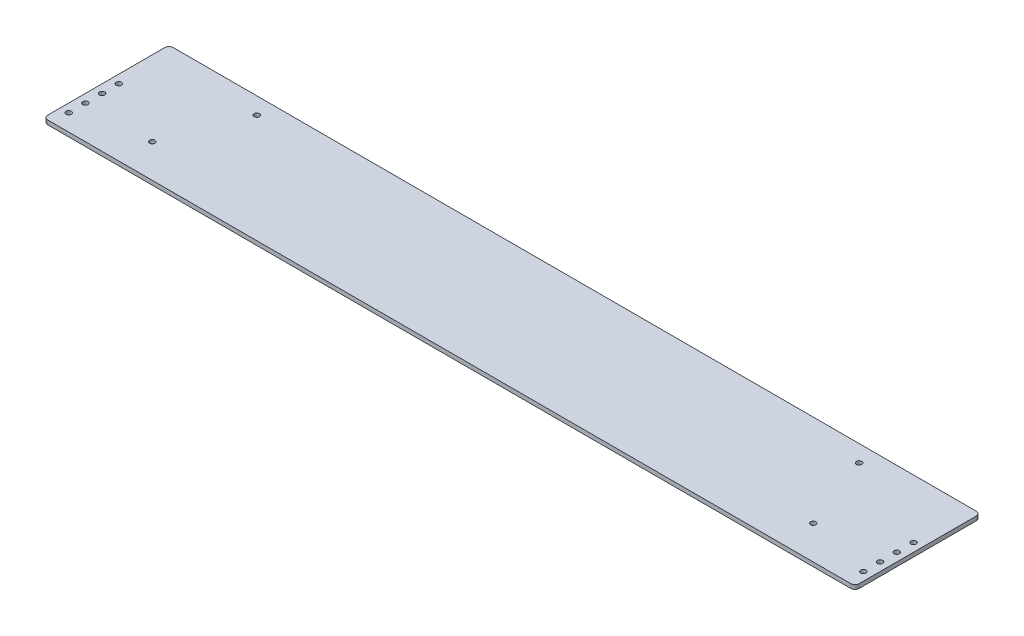
SolidWorks part; units mm, degrees
material "PC High Viscosity"
ref_plane "Front Plane" through (0, 0, 0) normal (0, 0, 1) x (1, 0, 0)
ref_plane "Top Plane" through (0, 0, 0) normal (0, 1, 0) x (1, 0, 0)
ref_plane "Right Plane" through (0, 0, 0) normal (1, 0, 0) x (0, 0, -1)
sketch "Sketch1" plane through (0, 0, 0) normal (0, 1, 0) x (1, 0, 0)
  line L0 (-301.625, 3.175) -> (-301.625, -34.925) construction
  line L1 (-307.975, -47.625) -> (307.975, -47.625)
  line L2 (-307.975, -47.625) -> (-307.975, 47.625)
  line L3 (-307.975, 47.625) -> (307.975, 47.625)
  line L4 (307.975, -47.625) -> (307.975, 47.625)
  line L5 (-307.975, -47.625) -> (307.975, 47.625) construction
  line L6 (-307.975, 47.625) -> (307.975, -47.625) construction
  line L7 (0, 47.625) -> (0, -47.625) construction
  circle A2 centre (-301.625, 3.175) radius 2.0193
  circle A3 centre (-301.625, -9.525) radius 2.0193
  circle A4 centre (-301.625, -22.225) radius 2.0193
  circle A5 centre (-301.625, -34.925) radius 2.0193
  circle A6 centre (301.625, -34.925) radius 2.0193
  circle A7 centre (301.625, -22.225) radius 2.0193
  circle A8 centre (301.625, -9.525) radius 2.0193
  circle A9 centre (301.625, 3.175) radius 2.0193
  point P0 (0, 0)
  dimension "D3" = 6.35
  dimension "D4" = 4.0386
  dimension "D5" = 4
  dimension "D6" = 44.45
  dimension "D7" = 12.7
  dimension "D1" = 95.25
  dimension "D2" = 615.95
extrude "Boss-Extrude1" add sketch "Sketch1" along normal blind 3.175
fillet "Fillet1" radius 3.175 4 edges at (307.975, 1.5875, 47.625) (-307.975, 1.5875, -47.625) (307.975, 1.5875, -47.625) (-307.975, 1.5875, 47.625)
sketch "Sketch2" plane through (0, 3.175, 0) normal (0, 1, 0) x (1, 0, 0)
  line L0 (304.8, 47.625) -> (-304.8, 47.625) construction
  line L1 (-307.975, 44.45) -> (-307.975, -44.45) construction
  line L2 (-304.8, -47.625) -> (304.8, -47.625) construction
  line L3 (0, 47.625) -> (0, -47.625) construction
  circle A0 centre (-228.6, 34.925) radius 2.0193
  circle A1 centre (-250.825, -22.225) radius 2.0193
  circle A2 centre (-250.825, -22.225) radius 25.4 construction
  circle A3 centre (-228.6, 34.925) radius 25.4 construction
  circle A4 centre (250.825, -22.225) radius 25.4 construction
  circle A5 centre (250.825, -22.225) radius 2.0193
  circle A6 centre (228.6, 34.925) radius 25.4 construction
  circle A7 centre (228.6, 34.925) radius 2.0193
  dimension "D1" = 4.0386
  dimension "D2" = 50.8
  dimension "D3" = 50.8
  dimension "D4" = 12.7
  dimension "D6" = 25.4
  dimension "D7" = 79.375
  dimension "D5" = 57.15
extrude "Cut-Extrude1" cut sketch "Sketch2" against normal through all
